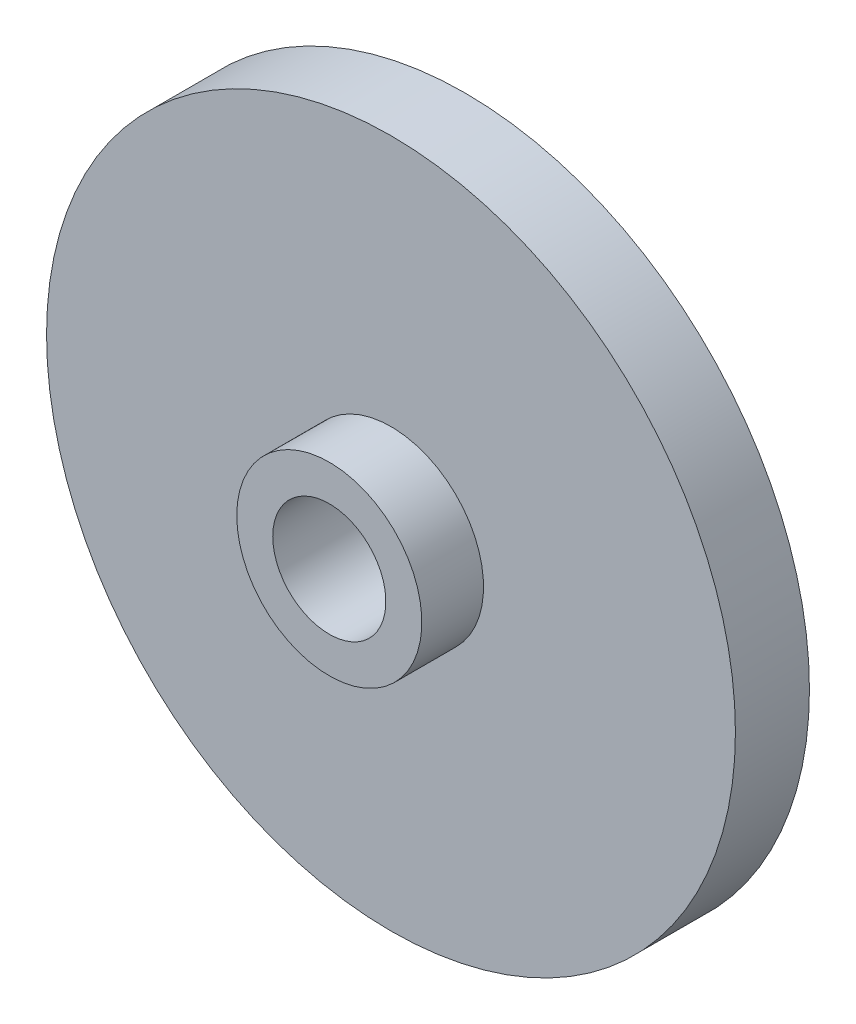
SolidWorks part; units mm, degrees
material "Настроенная пользователем пластмасса"
ref_plane "Спереди" through (0, 0, 0) normal (0, 0, 1) x (1, 0, 0)
ref_plane "Сверху" through (0, 0, 0) normal (0, 1, 0) x (1, 0, 0)
ref_plane "Справа" through (0, 0, 0) normal (1, 0, 0) x (0, 0, -1)
ref_plane "Плоскость4" through (0, 0, 0) normal (0, -1, 0) x (1, 0, 0)
sketch "Эскиз1" plane through (0, 0, 0) normal (0, -1, 0) x (1, 0, 0)
  line L0 (4.5, 6.6) -> (2.75, 6.6)
  line L1 (2.75, 6.6) -> (2.75, -5.5)
  line L2 (2.75, -5.5) -> (3.5, -5.5)
  line L3 (3.5, -5.5) -> (3.5, 0)
  line L4 (3.5, 0) -> (16.75, 0)
  line L5 (16.75, 0) -> (16.75, 3.6)
  line L6 (16.75, 3.6) -> (4.5, 3.6)
  line L7 (4.5, 3.6) -> (4.5, 6.6)
  line L8 (0, 6.6) -> (0, -5.5) construction
revolve "Повернуть1" add sketch "Эскиз1" angle 360 about L8
